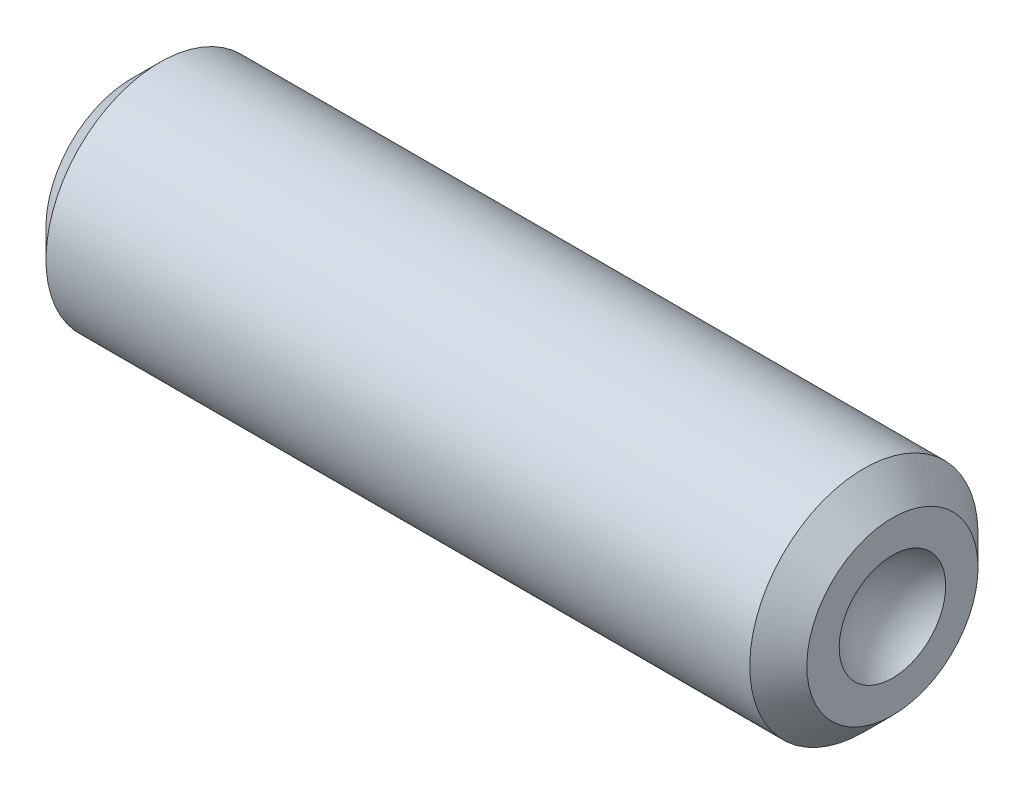
SolidWorks part; units mm, degrees
ref_plane "Front Plane" through (0, 0, 0) normal (0, 0, 1) x (1, 0, 0)
ref_plane "Top Plane" through (0, 0, 0) normal (0, 1, 0) x (1, 0, 0)
ref_plane "Right Plane" through (0, 0, 0) normal (1, 0, 0) x (0, 0, -1)
sketch "Sketch1" plane through (0, 0, 0) normal (0, 0, 1) x (1, 0, 0)
  line L0 (0, 0) -> (0, 1.125)
  line L1 (0, 1.125) -> (0.375, 1.5)
  line L2 (0.375, 1.5) -> (9.625, 1.5)
  line L3 (9.625, 1.5) -> (10, 1.125)
  line L4 (0, 0) -> (9.625, 0) construction
  line L5 (0.375, 1.5) -> (0.375, 1.125) construction
  line L6 (0.375, 1.125) -> (0.375, 0.75) construction
  line L7 (0.375, 0.75) -> (0.375, 0.375) construction
  line L8 (0.375, 0.375) -> (0.375, 0) construction
  line L9 (0.375, 1.125) -> (0, 1.125) construction
  line L10 (9.625, 1.5) -> (9.625, 0) construction
  line L11 (10, 1.125) -> (10, 0.7)
  line L12 (0, 0) -> (9.625, 0)
  arc A0 (9.625, 0) -> (10, 0.7) centre (10.4658, 0) cw
  dimension "D1" = 45
  dimension "D2" = 3
  dimension "D3" = 10
  dimension "D4" = 1.4
revolve "Revolve1" add sketch "Sketch1" angle 360 about L12
sketch "Sketch2" plane through (0, 0, 0) normal (-1, 0, 0) x (0, 0, 1)
  line L1 (0, 0.866) -> (-0.75, 0.433)
  line L2 (-0.75, 0.433) -> (-0.75, -0.433)
  line L3 (-0.75, -0.433) -> (0, -0.866)
  line L4 (0, -0.866) -> (0.75, -0.433)
  line L5 (0.75, -0.433) -> (0.75, 0.433)
  line L6 (0.75, 0.433) -> (0, 0.866)
  circle A0 centre (0, 0) radius 0.75 construction
  dimension "D1" = 1.5
extrude "Cut-Extrude1" cut sketch "Sketch2" against normal offset from surface (8 mm away) 2 up to face at (10, -1.125, 0)
